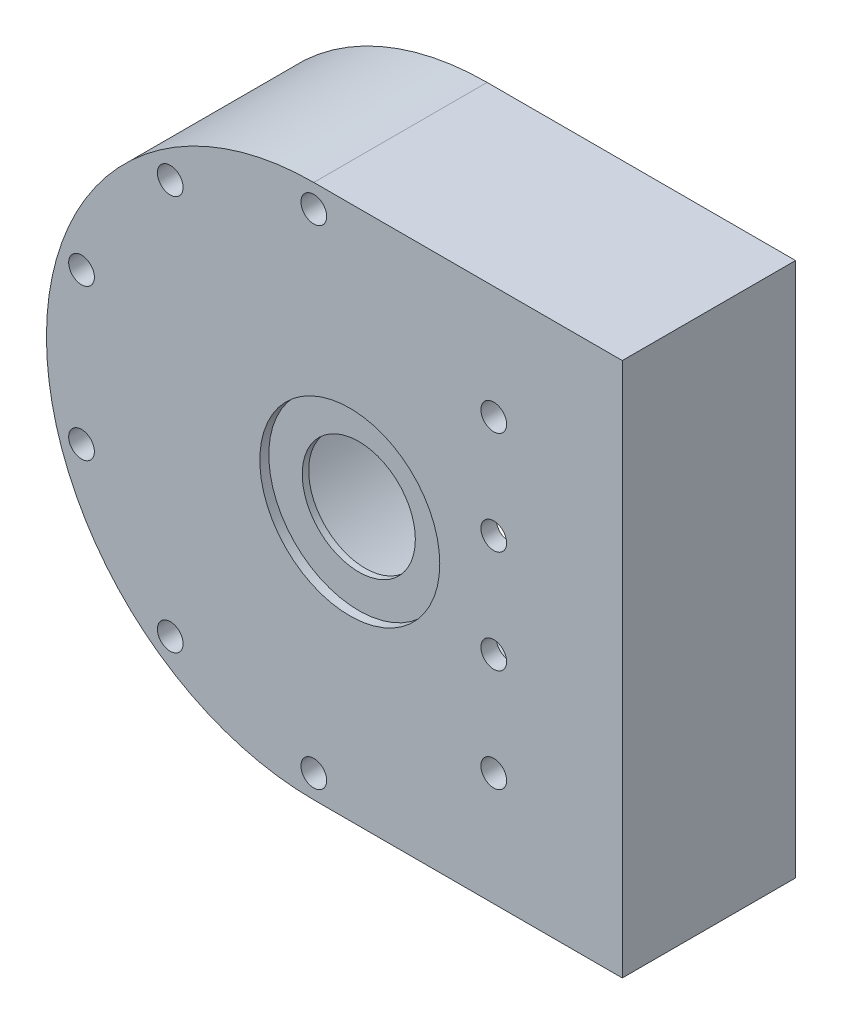
SolidWorks part; units mm, degrees
ref_plane "Alzado" through (0, 0, 0) normal (0, 0, 1) x (1, 0, 0)
ref_plane "Planta" through (0, 0, 0) normal (0, 1, 0) x (1, 0, 0)
ref_plane "Vista lateral" through (0, 0, 0) normal (1, 0, 0) x (0, 0, -1)
sketch "Croquis1" plane through (0, 0, 0) normal (0, 0, 1) x (1, 0, 0)
  line L3 (0, -52) -> (60, -52)
  line L4 (60, -52) -> (60, 52)
  line L5 (60, 52) -> (0, 52)
  line L6 (0, -52) -> (60, -52)
  line L7 (60, -52) -> (60, 52)
  line L8 (60, 52) -> (0, 52)
  circle A0 centre (7, 0) radius 30.25
  arc A2 (0, 52) -> (0, -52) centre (0, 0) ccw
  arc A3 (0, 52) -> (0, -52) centre (0, 0) ccw
  dimension "D1" = 60.5
  dimension "D2" = 0
extrude "Saliente-Extruir1" add sketch "Croquis1" along normal blind 30.7
sketch "Croquis2" plane through (0, 0, 30.7) normal (0, 0, 1) x (1, 0, 0)
  line L3 (0, -52) -> (60, -52)
  line L4 (60, -52) -> (60, 52)
  line L5 (60, 52) -> (0, 52)
  line L6 (0, -52) -> (60, -52)
  line L7 (60, -52) -> (60, 52)
  line L8 (60, 52) -> (0, 52)
  circle A0 centre (7, 0) radius 11
  arc A2 (0, 52) -> (0, -52) centre (0, 0) ccw
  arc A3 (0, 52) -> (0, -52) centre (0, 0) ccw
  dimension "D1" = 22
  dimension "D2" = 0
extrude "Saliente-Extruir2" add sketch "Croquis2" along normal blind 3
sketch "Croquis3" plane through (0, 0, 33.7) normal (0, 0, 1) x (1, 0, 0)
  circle A0 centre (7, 0) radius 17.5
  dimension "D1" = 35
extrude "Cortar-Extruir1" cut sketch "Croquis3" against normal blind 1.75
sketch "Croquis4" plane through (0, 0, 33.7) normal (0, 0, 1) x (1, 0, 0)
  circle A0 centre (35, 30) radius 2.5
  circle A1 centre (0, 0) radius 47.5 construction
  circle A2 centre (0, 47.5) radius 2.5
  circle A3 centre (-27.9198, 38.4283) radius 2.5
  circle A4 centre (-45.1752, 14.6783) radius 2.5
  circle A5 centre (-45.1752, -14.6783) radius 2.5
  circle A6 centre (-27.9198, -38.4283) radius 2.5
  circle A7 centre (0, -47.5) radius 2.5
  circle A8 centre (35, 10) radius 2.5
  circle A9 centre (35, -10) radius 2.5
  circle A10 centre (35, -30) radius 2.5
  point P19 (0, 0)
  dimension "D1" = 5
  dimension "D4" = 95
  dimension "D5" = 5
  dimension "D2" = 30
  dimension "D3" = 35
  dimension "D6" = 4
extrude "Cortar-Extruir2" cut sketch "Croquis4" against normal through all
